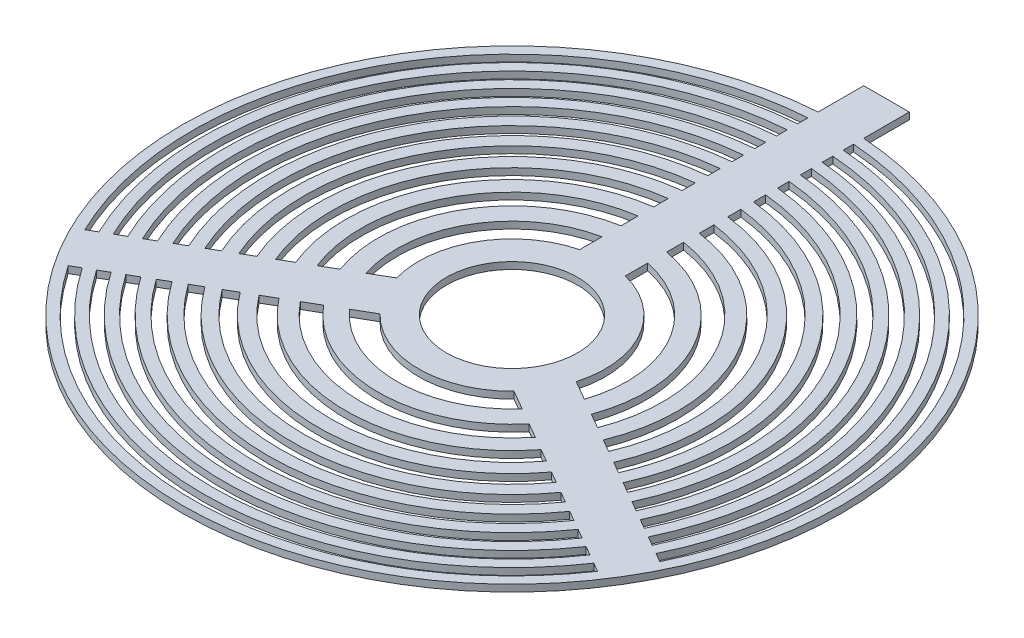
SolidWorks part; units mm, degrees
ref_plane "前视基准面" through (0, 0, 0) normal (0, 0, 1) x (1, 0, 0)
ref_plane "上视基准面" through (0, 0, 0) normal (0, 1, 0) x (1, 0, 0)
ref_plane "右视基准面" through (0, 0, 0) normal (1, 0, 0) x (0, 0, -1)
other "Configuration Table"
sketch "草图4" plane through (0, 0, 0) normal (0, 1, 0) x (1, 0, 0)
  line L0 (0, 25.4837) -> (0, 26.9762) construction
  line L1 (126.177, -61.3013) -> (122.2609, -59.0404)
  line L3 (-10, 139.9231) -> (-10, 135.4012)
  line L5 (10, 139.9231) -> (10, 135.4012)
  line L6 (116.177, -78.6218) -> (112.2609, -76.3609)
  line L7 (-116.177, -78.6218) -> (-112.2609, -76.3609)
  line L8 (-126.177, -61.3013) -> (-122.2609, -59.0404)
  line L9 (-110.1519, -52.0492) -> (-105.9542, -49.6257)
  line L10 (-118.292, -56.7489) -> (-114.2528, -54.4169)
  line L11 (-108.292, -74.0694) -> (-104.2528, -71.7374)
  line L12 (-100.1519, -69.3697) -> (-95.9542, -66.9462)
  line L13 (-101.677, -47.1562) -> (-97.2939, -44.6257)
  line L14 (-92.7872, -42.0237) -> (-88.1389, -39.34)
  line L15 (-83.331, -36.5642) -> (-78.319, -33.6705)
  line L16 (-73.0752, -30.643) -> (-67.5277, -27.4401)
  line L17 (-61.5854, -24.0093) -> (-55.119, -20.2759)
  line L18 (-47.8859, -16.0999) -> (-39.4079, -11.2052)
  line L19 (-37.8859, -33.4205) -> (-29.4079, -28.5257)
  line L20 (-51.5854, -41.3298) -> (-45.119, -37.5964)
  line L21 (-63.0752, -47.9635) -> (-57.5277, -44.7606)
  line L22 (-82.7872, -59.3442) -> (-78.1389, -56.6605)
  line L23 (-73.331, -53.8847) -> (-68.319, -50.991)
  line L24 (-91.677, -64.4768) -> (-87.2939, -61.9462)
  line L25 (-10, 49.5204) -> (-10, 39.7309)
  line L26 (10, 49.5204) -> (10, 39.7309)
  line L27 (10, 65.3392) -> (10, 57.8724)
  line L28 (10, 78.6065) -> (10, 72.2008)
  line L29 (-10, 78.6065) -> (-10, 72.2008)
  line L30 (-10, 65.3392) -> (-10, 57.8724)
  line L31 (-10, 90.4489) -> (-10, 84.6615)
  line L32 (10, 90.4489) -> (10, 84.6615)
  line L33 (-10, 101.3679) -> (-10, 96.0006)
  line L34 (10, 101.3679) -> (10, 96.0006)
  line L35 (-10, 111.633) -> (-10, 106.5719)
  line L36 (10, 111.633) -> (10, 106.5719)
  line L37 (-10, 121.4189) -> (-10, 116.5719)
  line L38 (10, 121.4189) -> (10, 116.5719)
  line L39 (-10, 130.8183) -> (-10, 126.1543)
  line L40 (10, 130.8183) -> (10, 126.1543)
  line L41 (47.8859, -16.0999) -> (39.4079, -11.2052)
  line L42 (37.8859, -33.4205) -> (29.4079, -28.5257)
  line L43 (61.5854, -24.0093) -> (55.119, -20.2759)
  line L44 (51.5854, -41.3298) -> (45.119, -37.5964)
  line L45 (73.0752, -30.643) -> (67.5277, -27.4401)
  line L46 (63.0752, -47.9635) -> (57.5277, -44.7606)
  line L47 (83.331, -36.5642) -> (78.319, -33.6705)
  line L48 (73.331, -53.8847) -> (68.319, -50.991)
  line L49 (92.7872, -42.0237) -> (88.1389, -39.34)
  line L50 (82.7872, -59.3442) -> (78.1389, -56.6605)
  line L51 (101.677, -47.1562) -> (97.2939, -44.6257)
  line L52 (91.677, -64.4768) -> (87.2939, -61.9462)
  line L53 (110.1519, -52.0492) -> (105.9542, -49.6257)
  line L54 (100.1519, -69.3697) -> (95.9542, -66.9462)
  line L55 (118.292, -56.7489) -> (114.2528, -54.4169)
  line L56 (108.292, -74.0694) -> (104.2528, -71.7374)
  line L57 (-10, 144.3741) -> (-10, 164.3741)
  line L58 (-10, 164.3741) -> (10, 164.3741)
  line L59 (10, 164.3741) -> (10, 144.3741)
  circle A0 centre (0, 0) radius 28.77
  arc A1 (-10, 39.7309) -> (-39.4079, -11.2052) centre (0, 0) ccw
  arc A2 (-10, 49.5204) -> (-47.8859, -16.0999) centre (0, 0) ccw
  arc A3 (-10, 57.8724) -> (-55.119, -20.2759) centre (0, 0) ccw
  arc A4 (-10, 65.3392) -> (-61.5854, -24.0093) centre (0, 0) ccw
  arc A5 (-10, 72.2008) -> (-67.5277, -27.4401) centre (0, 0) ccw
  arc A6 (-10, 84.6615) -> (-78.319, -33.6705) centre (0, 0) ccw
  arc A7 (-10, 90.4489) -> (-83.331, -36.5642) centre (0, 0) ccw
  arc A8 (-10, 96.0006) -> (-88.1389, -39.34) centre (0, 0) ccw
  arc A9 (-10, 78.6065) -> (-73.0752, -30.643) centre (0, 0) ccw
  arc A10 (-10, 101.3679) -> (-92.7872, -42.0237) centre (0, 0) ccw
  arc A11 (-10, 106.5719) -> (-97.2939, -44.6257) centre (0, 0) ccw
  arc A12 (102.0755, -46.2874) -> (-101.677, -47.1562) centre (0, 0) ccw
  arc A13 (-10, 111.633) -> (-101.677, -47.1562) centre (0, 0) ccw
  arc A14 (-10, 116.5719) -> (-105.9542, -49.6257) centre (0, 0) ccw
  arc A15 (-10, 121.4189) -> (-110.1519, -52.0492) centre (0, 0) ccw
  arc A16 (-10, 126.1543) -> (-114.2528, -54.4169) centre (0, 0) ccw
  arc A17 (-10, 130.8183) -> (-118.292, -56.7489) centre (0, 0) ccw
  arc A18 (-10, 135.4012) -> (-122.2609, -59.0404) centre (0, 0) ccw
  arc A19 (-10, 139.9231) -> (-126.177, -61.3013) centre (0, 0) ccw
  arc A20 (-10, 144.3741) -> (10, 144.3741) centre (0, 0) ccw
  arc A21 (39.4079, -11.2052) -> (10, 39.7309) centre (0, 0) ccw
  arc A22 (47.8859, -16.0999) -> (10, 49.5204) centre (0, 0) ccw
  arc A23 (55.119, -20.2759) -> (10, 57.8724) centre (0, 0) ccw
  arc A24 (61.5854, -24.0093) -> (10, 65.3392) centre (0, 0) ccw
  arc A25 (67.5277, -27.4401) -> (10, 72.2008) centre (0, 0) ccw
  arc A26 (73.0752, -30.643) -> (10, 78.6065) centre (0, 0) ccw
  arc A27 (78.319, -33.6705) -> (10, 84.6615) centre (0, 0) ccw
  arc A28 (83.331, -36.5642) -> (10, 90.4489) centre (0, 0) ccw
  arc A29 (88.1389, -39.34) -> (10, 96.0006) centre (0, 0) ccw
  arc A30 (92.7872, -42.0237) -> (10, 101.3679) centre (0, 0) ccw
  arc A31 (97.2939, -44.6257) -> (10, 106.5719) centre (0, 0) ccw
  arc A32 (101.677, -47.1562) -> (10, 111.633) centre (0, 0) ccw
  arc A33 (101.677, -47.1562) -> (10, 111.633) centre (0, 0) ccw
  arc A34 (105.9542, -49.6257) -> (10, 116.5719) centre (0, 0) ccw
  arc A35 (110.1519, -52.0492) -> (10, 121.4189) centre (0, 0) ccw
  arc A36 (114.2528, -54.4169) -> (10, 126.1543) centre (0, 0) ccw
  arc A37 (118.292, -56.7489) -> (10, 130.8183) centre (0, 0) ccw
  arc A38 (122.2609, -59.0404) -> (10, 135.4012) centre (0, 0) ccw
  arc A39 (126.177, -61.3013) -> (10, 139.9231) centre (0, 0) ccw
  arc A40 (-29.4079, -28.5257) -> (29.4079, -28.5257) centre (0, 0) ccw
  arc A41 (-37.8859, -33.4205) -> (37.8859, -33.4205) centre (0, 0) ccw
  arc A42 (-45.119, -37.5964) -> (45.119, -37.5964) centre (0, 0) ccw
  arc A43 (-51.5854, -41.3298) -> (51.5854, -41.3298) centre (0, 0) ccw
  arc A44 (-57.5277, -44.7606) -> (57.5277, -44.7606) centre (0, 0) ccw
  arc A45 (-63.0752, -47.9635) -> (63.0752, -47.9635) centre (0, 0) ccw
  arc A46 (-68.319, -50.991) -> (68.319, -50.991) centre (0, 0) ccw
  arc A47 (-73.331, -53.8847) -> (73.331, -53.8847) centre (0, 0) ccw
  arc A48 (-78.1389, -56.6605) -> (78.1389, -56.6605) centre (0, 0) ccw
  arc A49 (-82.7872, -59.3442) -> (82.7872, -59.3442) centre (0, 0) ccw
  arc A50 (-87.2939, -61.9462) -> (87.2939, -61.9462) centre (0, 0) ccw
  arc A51 (-91.677, -64.4768) -> (91.677, -64.4768) centre (0, 0) ccw
  arc A52 (-91.677, -64.4768) -> (91.677, -64.4768) centre (0, 0) ccw
  arc A53 (-95.9542, -66.9462) -> (95.9542, -66.9462) centre (0, 0) ccw
  arc A54 (-100.1519, -69.3697) -> (100.1519, -69.3697) centre (0, 0) ccw
  arc A55 (-104.2528, -71.7374) -> (104.2528, -71.7374) centre (0, 0) ccw
  arc A56 (-108.292, -74.0694) -> (108.292, -74.0694) centre (0, 0) ccw
  arc A57 (-112.2609, -76.3609) -> (112.2609, -76.3609) centre (0, 0) ccw
  arc A58 (-116.177, -78.6218) -> (116.177, -78.6218) centre (0, 0) ccw
  point P4 (0, 0)
  point P40 (0, 0)
  dimension "D1" = 57.54
  dimension "D2" = 81.94
  dimension "D3" = 101.04
  dimension "D4" = 117.46
  dimension "D5" = 132.2
  dimension "D6" = 145.78
  dimension "D7" = 158.48
  dimension "D8" = 170.5
  dimension "D9" = 182
  dimension "D10" = 193.04
  dimension "D11" = 203.72
  dimension "D12" = 214.08
  dimension "D13" = 224.16
  dimension "D14" = 20
  dimension "D15" = 234
  dimension "D16" = 243.66
  dimension "D17" = 253.1
  dimension "D18" = 262.4
  dimension "D19" = 271.54
  dimension "D20" = 280.56
  dimension "D21" = 289.44
  dimension "D22" = 20
  dimension "D23" = 3
extrude "凸台-拉伸1" add sketch "草图4" along normal blind 3 contours L57 A20 L59 L58 A58 L7 A57 L6 A56 L11 A55 L56 A54 L12 A53 L54 A51 L24 A50 L52 A49 L22 A48 L50 A47 L23 A46 L48 A45 L21 A44 L46 A43 L20 A42 L44 A41 L19 A40 L42 A39
